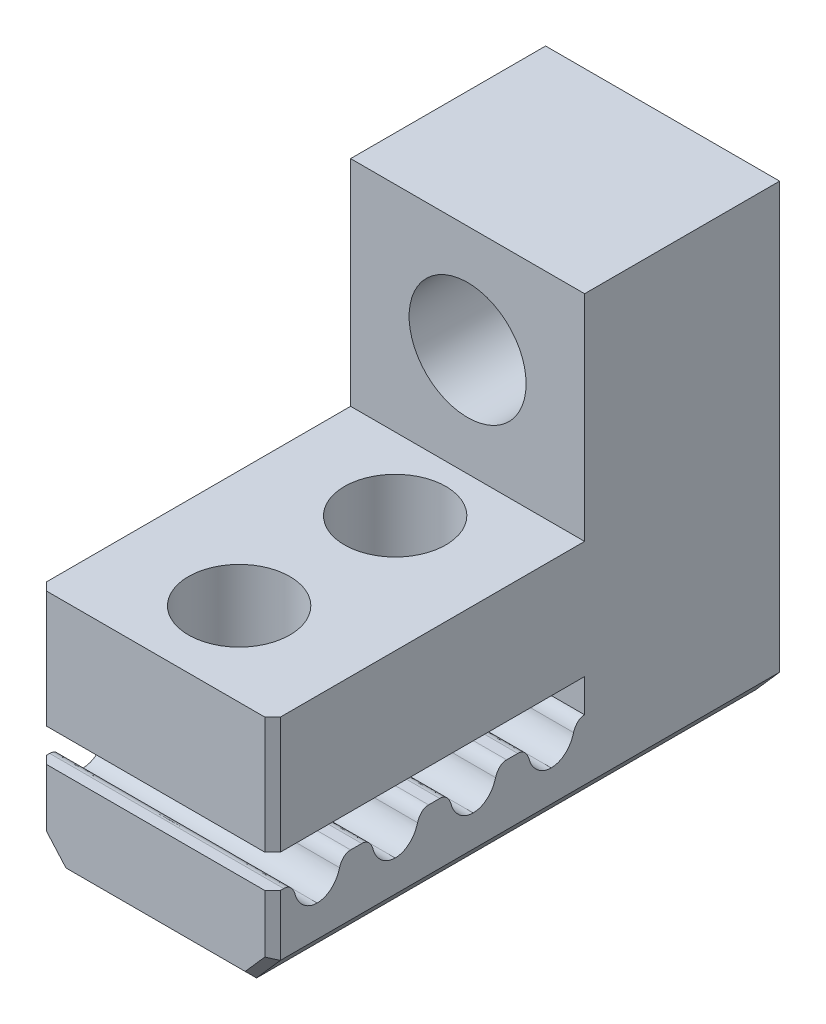
SolidWorks part; units mm, degrees
ref_plane "Front Plane" through (0, 0, 0) normal (0, 0, 1) x (1, 0, 0)
ref_plane "Top Plane" through (0, 0, 0) normal (0, 1, 0) x (1, 0, 0)
ref_plane "Right Plane" through (0, 0, 0) normal (1, 0, 0) x (0, 0, -1)
sketch "Sketch1" plane through (0, 0, 0) normal (0, 0, 1) x (1, 0, 0)
  line L0 (3, 3.05) -> (3, -2.2538)
  line L1 (-3, 3.05) -> (-3, -2.2538)
  line L7 (-3, 3.05) -> (3, 3.05)
  line L13 (-3, -2.2538) -> (-2.3882, -2.95)
  line L14 (3, -2.2538) -> (2.3882, -2.95)
  line L16 (-2.3882, -2.95) -> (2.3882, -2.95)
extrude "Boss-Extrude1" add sketch "Sketch1" along normal blind 13
sketch "Sketch6" plane through (0, 3.05, 0) normal (0, 1, 0) x (1, 0, 0)
  line L1 (-3, 0) -> (3, 0)
  line L2 (-3, 0) -> (-3, -5)
  line L3 (-3, -5) -> (3, -5)
  line L4 (3, 0) -> (3, -5)
  line L7 (3, 0) -> (-3, 0) construction
  line L9 (3, -13) -> (3, 0) construction
  line L10 (-3, -13) -> (-3, 0) construction
extrude "Boss-Extrude4" add sketch "Sketch6" along normal blind 5.6
sketch "Sketch16" plane through (0, 3.05, 0) normal (0, 1, 0) x (1, 0, 0)
  line L4 (3, -5) -> (-3, -5)
  line L5 (-3, -5) -> (-3, -13)
  line L6 (-3, -13) -> (3, -13)
  line L7 (3, -13) -> (3, -5)
  line L8 (3, -5) -> (-3, -5)
  line L9 (-3, -5) -> (-3, -13)
  line L10 (-3, -13) -> (3, -13)
  line L11 (3, -13) -> (3, -5)
  dimension "D1" = 0
extrude "Boss-Extrude5" add sketch "Sketch16" along normal blind 0.1
sketch "Sketch18" plane through (0, 0, 0) normal (1, 0, 0) x (0, 0, -1)
  line L0 (-8.8572, -0.0702) -> (-12.8572, -0.0702)
  line L2 (-12.8572, -0.7) -> (-12.7144, -0.7)
  line L3 (-11, -0.7) -> (-10.8572, -0.7)
  line L4 (-10.8572, -0.7) -> (-10.7144, -0.7)
  line L5 (-9, -0.7) -> (-8.8572, -0.7)
  line L6 (-8.8572, -0.7) -> (-8.7144, -0.7)
  line L7 (-7, -0.7) -> (-6.8572, -0.7)
  line L8 (-6.8572, -0.7) -> (-6.7144, -0.7)
  line L9 (-5, -0.0702) -> (-5, -0.7)
  line L11 (-5, -0.0702) -> (-8.8572, -0.0702)
  line L12 (-13, -2.95) -> (0, -2.95) construction
  line L13 (-5.8572, -1.45) -> (-5, -1.45) construction
  line L14 (-5, -1.45) -> (-11.8572, -1.45) construction
  line L15 (-5, 3.15) -> (-5, -1.45) construction
  line L16 (-5, -0.7) -> (-5, -1.45) construction
  line L17 (-12.8572, -0.0702) -> (-13, -0.0702)
  line L20 (-13, -0.0702) -> (-13, -0.7)
  line L22 (-12.8572, -0.7) -> (-13, -0.7)
  spline S0 degree 2 poles (-12.7144, -0.7) (-12.5198, -0.7) (-12.43, -0.9509) knots 0.103448 0.103448 0.103448 0.137931 0.137931 0.137931
  spline S1 degree 3 poles (-12.43, -0.9509) (-12.3594, -1.2388) (-12.13, -1.45) (-11.8572, -1.45) knots 0.137931 0.137931 0.137931 0.137931 0.172414 0.172414 0.172414 0.172414
  spline S2 degree 3 poles (-11.8572, -1.45) (-11.5844, -1.45) (-11.355, -1.2388) (-11.2844, -0.9509) knots 0.172414 0.172414 0.172414 0.172414 0.206897 0.206897 0.206897 0.206897
  spline S3 degree 2 poles (-11.2844, -0.9509) (-11.1946, -0.7) (-11, -0.7) knots 0.206897 0.206897 0.206897 0.241379 0.241379 0.241379
  spline S4 degree 2 poles (-10.7144, -0.7) (-10.5198, -0.7) (-10.43, -0.9509) knots 0.310345 0.310345 0.310345 0.344828 0.344828 0.344828
  spline S5 degree 3 poles (-10.43, -0.9509) (-10.3594, -1.2388) (-10.13, -1.45) (-9.8572, -1.45) knots 0.344828 0.344828 0.344828 0.344828 0.37931 0.37931 0.37931 0.37931
  spline S6 degree 3 poles (-9.8572, -1.45) (-9.5844, -1.45) (-9.355, -1.2388) (-9.2844, -0.9509) knots 0.37931 0.37931 0.37931 0.37931 0.413793 0.413793 0.413793 0.413793
  spline S7 degree 2 poles (-9.2844, -0.9509) (-9.1946, -0.7) (-9, -0.7) knots 0.413793 0.413793 0.413793 0.448276 0.448276 0.448276
  spline S8 degree 2 poles (-8.7144, -0.7) (-8.5198, -0.7) (-8.43, -0.9509) knots 0.517241 0.517241 0.517241 0.551724 0.551724 0.551724
  spline S9 degree 3 poles (-8.43, -0.9509) (-8.3594, -1.2388) (-8.13, -1.45) (-7.8572, -1.45) knots 0.551724 0.551724 0.551724 0.551724 0.586207 0.586207 0.586207 0.586207
  spline S10 degree 3 poles (-7.8572, -1.45) (-7.5844, -1.45) (-7.355, -1.2388) (-7.2844, -0.9509) knots 0.586207 0.586207 0.586207 0.586207 0.62069 0.62069 0.62069 0.62069
  spline S11 degree 2 poles (-7.2844, -0.9509) (-7.1946, -0.7) (-7, -0.7) knots 0.62069 0.62069 0.62069 0.655172 0.655172 0.655172
  spline S12 degree 2 poles (-6.7144, -0.7) (-6.5198, -0.7) (-6.43, -0.9509) knots 0.724138 0.724138 0.724138 0.758621 0.758621 0.758621
  spline S13 degree 3 poles (-6.43, -0.9509) (-6.3594, -1.2388) (-6.13, -1.45) (-5.8572, -1.45) knots 0.758621 0.758621 0.758621 0.758621 0.793103 0.793103 0.793103 0.793103
  spline S14 degree 3 poles (-5.8572, -1.45) (-5.5844, -1.45) (-5.355, -1.2388) (-5.2844, -0.9509) knots 0.793103 0.793103 0.793103 0.793103 0.827586 0.827586 0.827586 0.827586
  spline S15 degree 2 poles (-5.2844, -0.9509) (-5.1946, -0.7) (-5, -0.7) knots 0.827586 0.827586 0.827586 0.862069 0.862069 0.862069
  dimension "D1" = 1.5
  dimension "D2" = 1.3798
extrude "Cut-Extrude6" cut sketch "Sketch18" against normal blind 3.6 and the other way blind 4
sketch "Sketch15" plane through (0, 8.65, 0) normal (0, 1, 0) x (1, 0, 0)
  line L0 (0, -13) -> (0, -5) construction
  line L1 (-3, -13) -> (3, -13) construction
  line L2 (-3, -5) -> (3, -5) construction
  line L3 (2.008, -10.7144) -> (2.008, -11) construction
  line L4 (3, -10.7144) -> (-3, -10.7144) construction
  line L5 (3, -11) -> (-3, -11) construction
  line L6 (2.008, -10.8572) -> (0, -10.8572) construction
  line L7 (1.0382, -6.7144) -> (1.0382, -7) construction
  line L8 (3, -6.7144) -> (-3, -6.7144) construction
  line L9 (3, -7) -> (-3, -7) construction
  line L10 (1.0382, -6.8572) -> (0, -6.8572) construction
  circle A0 centre (0, -6.8572) radius 1.5 construction
  circle A1 centre (0, -10.8572) radius 1.5 construction
  circle A2 centre (0, -10.8572) radius 1.3
  circle A4 centre (0, -6.8572) radius 1.3
  dimension "D1" = 2.6
  dimension "D2" = 2.6
extrude "Cut-Extrude7" cut sketch "Sketch15" against normal up to surface (8.7202 mm away) up to face at (0, -0.0702, 9)
sketch "Sketch19" plane through (0, -0.0702, 0) normal (0, -1, 0) x (1, 0, 0)
  line L4 (-3, 13) -> (-3, 5)
  line L5 (-3, 5) -> (3, 5)
  line L6 (3, 5) -> (3, 13)
  line L7 (3, 13) -> (-3, 13)
  line L8 (-3, 13) -> (-3, 5)
  line L9 (-3, 5) -> (3, 5)
  line L10 (3, 5) -> (3, 13)
  line L11 (3, 13) -> (-3, 13)
  circle A0 centre (0, 10.8572) radius 1.3 construction
  circle A1 centre (0, 6.8572) radius 1.3 construction
  circle A2 centre (0, 10.8572) radius 1.3
  circle A3 centre (0, 6.8572) radius 1.3
  dimension "D1" = 0
extrude "Cut-Extrude8" cut sketch "Sketch19" against normal blind 0.2202
sketch "Sketch12" plane through (0, 0, 5) normal (0, 0, 1) x (1, 0, 0)
  line L0 (-3, 5.9) -> (0, 5.9) construction
  line L1 (-3, 8.65) -> (-3, 3.15) construction
  line L2 (0, 5.9) -> (0, 8.65) construction
  line L3 (-3, 8.65) -> (3, 8.65) construction
  circle A0 centre (0, 5.9) radius 1.5 construction
  circle A1 centre (0, 5.9) radius 1.5
  dimension "D1" = 3
extrude "Cut-Extrude5" cut sketch "Sketch12" against normal blind 6
chamfer "Chamfer1" distance 0.2 angle 45 7 edges at (-3, 1.65, 13) (3, 1.65, 13) (3, -1.4769, 13) (2.6941, -2.6019, 13) (-3, -1.4769, 13) (-2.6941, -2.6019, 13) (0, -2.95, 13)
sketch "Sketch20" plane through (3, 0, 0) normal (1, 0, 0) x (0, 0, -1)
  line L1 (-5, 3.15) -> (0, 3.15)
  line L2 (-5, 3.15) -> (-5, 8.65)
  line L3 (-5, 8.65) -> (0, 8.65)
  line L4 (0, 3.15) -> (0, 8.65)
extrude "Boss-Extrude6" add sketch "Sketch20" along normal blind 0.5
sketch "Sketch21" plane through (-3, 0, 0) normal (-1, 0, 0) x (0, 0, 1)
  line L1 (5, 3.15) -> (0, 3.15)
  line L2 (5, 3.15) -> (5, 8.65)
  line L3 (5, 8.65) -> (0, 8.65)
  line L4 (0, 3.15) -> (0, 8.65)
extrude "Boss-Extrude7" add sketch "Sketch21" along normal blind 0.5
chamfer "Chamfer2" distance 0.2 angle 45 2 edges at (-3.5, 5.9, 5) (3.5, 5.9, 5)
sketch "Croquis1" plane through (-3.5, 0, 0) normal (-1, 0, 0) x (0, 0, 1)
  line L1 (5, 3.15) -> (0, 3.15)
  line L2 (5, 3.15) -> (5, 8.65)
  line L3 (5, 8.65) -> (0, 8.65)
  line L4 (0, 3.15) -> (0, 8.65)
extrude "Cortar-Extruir1" cut sketch "Croquis1" against normal up to surface (0.5 mm away) up to face at (-3, -0.5166, 8.3898)
sketch "Croquis2" plane through (3, 0, 0) normal (1, 0, 0) x (0, 0, -1)
  line L1 (0, 3.15) -> (-5, 3.15)
  line L2 (0, 3.15) -> (0, 8.65)
  line L3 (0, 8.65) -> (-5, 8.65)
  line L4 (-5, 3.15) -> (-5, 8.65)
  point P5 (-5, 8.65)
extrude "Cortar-Extruir2" cut sketch "Croquis2" along normal blind 1
